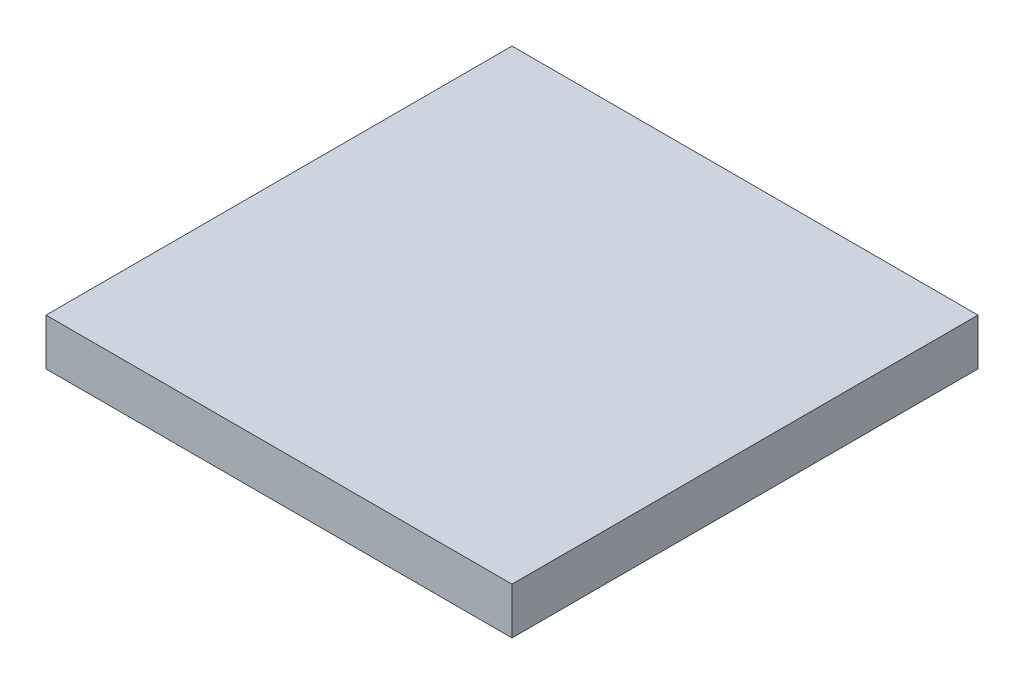
SolidWorks part; units mm, degrees
ref_plane "Alzado" through (0, 0, 0) normal (0, 0, 1) x (1, 0, 0)
ref_plane "Planta" through (0, 0, 0) normal (0, 1, 0) x (1, 0, 0)
ref_plane "Vista lateral" through (0, 0, 0) normal (1, 0, 0) x (0, 0, -1)
sketch "Croquis1" plane through (0, 0, 0) normal (0, 1, 0) x (1, 0, 0)
  line L1 (0, 0) -> (5, 0)
  line L2 (0, 0) -> (0, 5)
  line L3 (0, 5) -> (5, 5)
  line L4 (5, 0) -> (5, 5)
  dimension "D1" = 5
extrude "Saliente-Extruir1" add sketch "Croquis1" along normal blind 0.5
